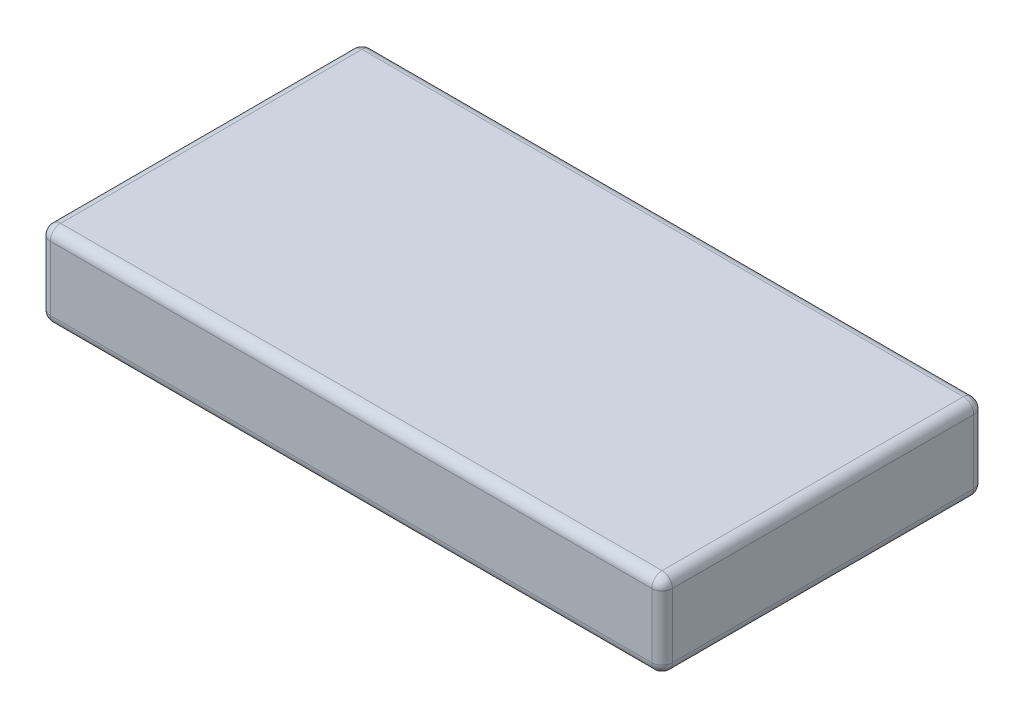
SolidWorks part; units mm, degrees
ref_plane "前视基准面" through (0, 0, 0) normal (0, 0, 1) x (1, 0, 0)
ref_plane "上视基准面" through (0, 0, 0) normal (0, 1, 0) x (1, 0, 0)
ref_plane "右视基准面" through (0, 0, 0) normal (1, 0, 0) x (0, 0, -1)
sketch "草图1" plane through (0, 0, 0) normal (0, 0, 1) x (1, 0, 0)
  line L1 (-30.05, -4.1) -> (30.05, -4.1)
  line L2 (-30.05, -4.1) -> (-30.05, 4.1)
  line L3 (-30.05, 4.1) -> (30.05, 4.1)
  line L4 (30.05, -4.1) -> (30.05, 4.1)
  line L5 (-30.05, -4.1) -> (30.05, 4.1) construction
  line L6 (-30.05, 4.1) -> (30.05, -4.1) construction
  point P0 (0, 0)
  dimension "D1" = 8.2
  dimension "D2" = 60.1
extrude "凸台-拉伸1" add sketch "草图1" along normal mid plane 31.1
fillet "圆角1" radius 1 12 edges at (30.05, 4.1, 0) (-30.05, 4.1, 0) (-30.05, -4.1, 0) (30.05, -4.1, 0) (0, -4.1, 15.55) (-30.05, 0, 15.55) (0, 4.1, 15.55) (30.05, 0, 15.55) (0, -4.1, -15.55) (-30.05, 0, -15.55) (0, 4.1, -15.55) (30.05, 0, -15.55)
